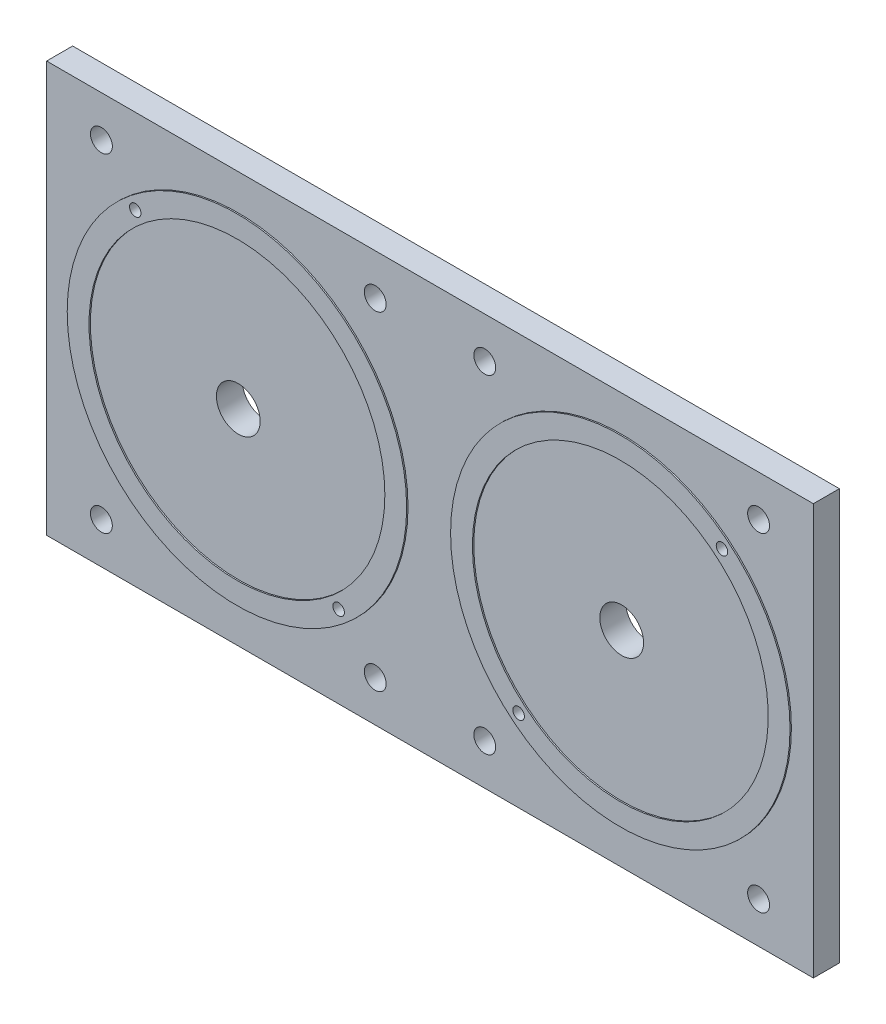
SolidWorks part; units mm, degrees
ref_plane "Plan de face" through (0, 0, 0) normal (0, 0, 1) x (1, 0, 0)
ref_plane "Plan de dessus" through (0, 0, 0) normal (0, 1, 0) x (1, 0, 0)
ref_plane "Plan de droite" through (0, 0, 0) normal (1, 0, 0) x (0, 0, -1)
sketch "Esquisse1" plane through (0, 0, 0) normal (0, 0, 1) x (1, 0, 0)
  line L1 (0, 0) -> (140, 0)
  line L2 (0, 0) -> (0, 75)
  line L3 (0, 75) -> (140, 75)
  line L4 (140, 0) -> (140, 75)
  dimension "D1" = 140
  dimension "D2" = 75
extrude "Boss.-Extru.1" add sketch "Esquisse1" along normal blind 4.75
sketch "Esquisse2" plane through (0, 0, 4.75) normal (0, 0, 1) x (1, 0, 0)
  line L0 (35, 37.5) -> (70, 37.5) construction
  line L1 (70, 37.5) -> (70, 75) construction
  line L2 (140, 75) -> (0, 75) construction
  line L3 (35, 37.5) -> (0, 37.5) construction
  line L4 (0, 75) -> (0, 0) construction
  circle A0 centre (35, 37.5) radius 30.99
  circle A1 centre (105, 37.5) radius 30.99
  circle A2 centre (35, 37.5) radius 27.01
  circle A3 centre (105, 37.5) radius 27.01
  dimension "D1" = 61.98
  dimension "D3" = 54.02
  dimension "D2" = 35
extrude "Boss.-Extru.2" add sketch "Esquisse2" along normal blind 0.25
sketch "Esquisse3" plane through (0, 0, 4.75) normal (0, 0, 1) x (1, 0, 0)
  line L0 (70, 0) -> (70, 75) construction
  line L1 (0, 0) -> (140, 0) construction
  line L2 (140, 75) -> (0, 75) construction
  line L3 (70, 75) -> (70, 37.5) construction
  line L4 (70, 37.5) -> (0, 37.5) construction
  line L5 (0, 75) -> (0, 0) construction
  line L6 (60, 67.5) -> (10, 67.5) construction
  line L7 (60, 7.5) -> (10, 7.5) construction
  line L8 (80, 7.5) -> (130, 7.5) construction
  line L9 (80, 67.5) -> (130, 67.5) construction
  line L10 (10, 67.5) -> (35, 37.5) construction
  line L11 (17.7086, 58.2497) -> (15.1607, 61.3072) construction
  line L12 (35, 37.5) -> (42.9618, 44.1349) construction
  circle A0 centre (10, 67.5) radius 2
  circle A1 centre (60, 67.5) radius 2
  circle A2 centre (60, 7.5) radius 2
  circle A3 centre (10, 7.5) radius 2
  circle A4 centre (130, 7.5) radius 2
  circle A5 centre (80, 7.5) radius 2
  circle A6 centre (80, 67.5) radius 2
  circle A7 centre (130, 67.5) radius 2
  circle A8 centre (35, 37.5) radius 4
  circle A9 centre (105, 37.5) radius 4
  circle A10 centre (35, 37.5) radius 27.01 construction
  circle A11 centre (35, 37.5) radius 30.99 construction
  circle A12 centre (16.4347, 59.7784) radius 1.05
  circle A13 centre (53.5653, 15.2216) radius 1.05
  circle A14 centre (123.5653, 59.7784) radius 1.05
  circle A15 centre (86.4347, 15.2216) radius 1.05
  point P39 (16.4347, 59.7784)
  dimension "D1" = 60
  dimension "D2" = 30
  dimension "D3" = 4
  dimension "D4" = 10
  dimension "D5" = 8
  dimension "D6" = 2.1
extrude "Enlèv. mat.-Extru.1" cut sketch "Esquisse3" against normal through all both and the other way through all
